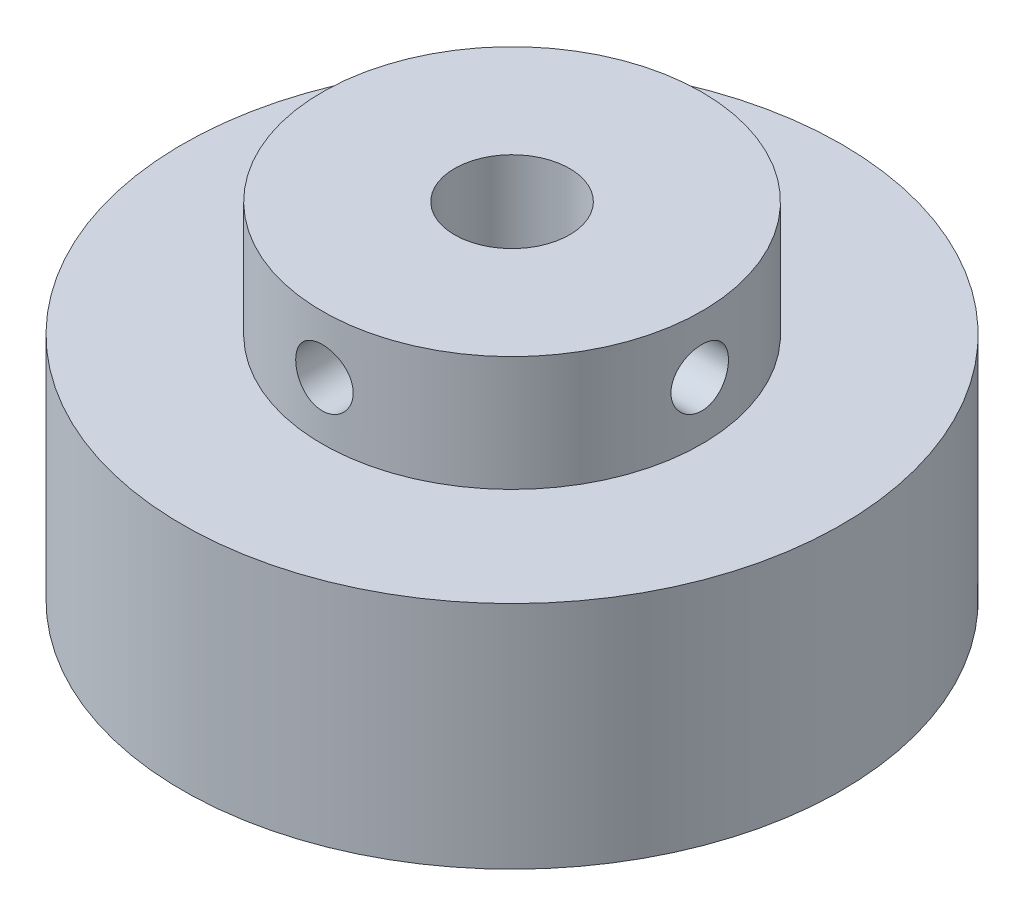
SolidWorks part; units mm, degrees
material "AISI 1020"
ref_plane "Alzado" through (0, 0, 0) normal (0, 0, 1) x (1, 0, 0)
ref_plane "Planta" through (0, 0, 0) normal (0, 1, 0) x (1, 0, 0)
ref_plane "Vista lateral" through (0, 0, 0) normal (1, 0, 0) x (0, 0, -1)
sketch "Croquis1" plane through (0, 0, 0) normal (0, 0, 1) x (1, 0, 0)
  line L0 (0, 0) -> (0, 49.1188) construction
  line L1 (-4, 0) -> (-4, 30)
  line L2 (-4, 30) -> (-16.5, 30)
  line L3 (-16.5, 30) -> (-16.5, 20)
  line L4 (-16.5, 20) -> (-28.65, 20)
  line L5 (-28.65, 20) -> (-28.65, 0)
  line L6 (-28.65, 0) -> (-4, 0)
  line L7 (0, 0) -> (29.4511, 0) construction
  dimension "D1" = 4
  dimension "D2" = 16.5
  dimension "D3" = 28.65
  dimension "D4" = 20
  dimension "D5" = 10
revolve "Revolución1" add sketch "Croquis1" angle 360 about L0
sketch "Croquis2" plane through (0, 0, 0) normal (0, -1, 0) x (-1, 0, 0)
  line L0 (0, 0) -> (0, -28.65) construction
  line L1 (0, 0) -> (-2.9947, -28.4931) construction
  line L2 (0, 0) -> (-5.9567, -28.0239) construction
  line L3 (0, 0) -> (-8.8533, -27.2478) construction
  line L4 (0, 0) -> (-11.653, -26.1731) construction
  line L5 (0, 0) -> (-14.325, -24.8116) construction
  line L6 (0, 0) -> (-16.84, -23.1783) construction
  line L7 (0, 0) -> (-19.1706, -21.2911) construction
  line L8 (0, 0) -> (-21.2911, -19.1706) construction
  line L9 (0, 0) -> (-23.1783, -16.84) construction
  line L10 (0, 0) -> (-24.8116, -14.325) construction
  line L11 (0, 0) -> (-26.1731, -11.653) construction
  line L12 (0, 0) -> (-27.2478, -8.8533) construction
  line L13 (0, 0) -> (-28.0239, -5.9567) construction
  line L14 (0, 0) -> (-28.4931, -2.9947) construction
  line L15 (0, 0) -> (-28.65, 0) construction
  line L16 (0, 0) -> (-28.4931, 2.9947) construction
  line L17 (0, 0) -> (-28.0239, 5.9567) construction
  line L18 (0, 0) -> (-27.2478, 8.8533) construction
  line L19 (0, 0) -> (-26.1731, 11.653) construction
  line L20 (0, 0) -> (-24.8116, 14.325) construction
  line L21 (0, 0) -> (-23.1783, 16.84) construction
  line L22 (0, 0) -> (-21.2911, 19.1706) construction
  line L23 (0, 0) -> (-19.1706, 21.2911) construction
  line L24 (0, 0) -> (-16.84, 23.1783) construction
  line L25 (0, 0) -> (-14.325, 24.8116) construction
  line L26 (0, 0) -> (-11.653, 26.1731) construction
  line L27 (0, 0) -> (-8.8533, 27.2478) construction
  line L28 (0, 0) -> (-5.9567, 28.0239) construction
  line L29 (0, 0) -> (-2.9947, 28.4931) construction
  line L30 (0, 0) -> (0, 28.65) construction
  line L31 (0, 0) -> (2.9947, 28.4931) construction
  line L32 (0, 0) -> (5.9567, 28.0239) construction
  line L33 (0, 0) -> (8.8533, 27.2478) construction
  line L34 (0, 0) -> (11.653, 26.1731) construction
  line L35 (0, 0) -> (14.325, 24.8116) construction
  line L36 (0, 0) -> (16.84, 23.1783) construction
  line L37 (0, 0) -> (19.1706, 21.2911) construction
  line L38 (0, 0) -> (21.2911, 19.1706) construction
  line L39 (0, 0) -> (23.1783, 16.84) construction
  line L40 (0, 0) -> (24.8116, 14.325) construction
  line L41 (0, 0) -> (26.1731, 11.653) construction
  line L42 (0, 0) -> (27.2478, 8.8533) construction
  line L43 (0, 0) -> (28.0239, 5.9567) construction
  line L44 (0, 0) -> (28.4931, 2.9947) construction
  line L45 (0, 0) -> (28.65, 0) construction
  line L46 (0, 0) -> (28.4931, -2.9947) construction
  line L47 (0, 0) -> (28.0239, -5.9567) construction
  line L48 (0, 0) -> (27.2478, -8.8533) construction
  line L49 (0, 0) -> (26.1731, -11.653) construction
  line L50 (0, 0) -> (24.8116, -14.325) construction
  line L51 (0, 0) -> (23.1783, -16.84) construction
  line L52 (0, 0) -> (21.2911, -19.1706) construction
  line L53 (0, 0) -> (19.1706, -21.2911) construction
  line L54 (0, 0) -> (16.84, -23.1783) construction
  line L55 (0, 0) -> (14.325, -24.8116) construction
  line L56 (0, 0) -> (11.653, -26.1731) construction
  line L57 (0, 0) -> (8.8533, -27.2478) construction
  line L58 (0, 0) -> (5.9567, -28.0239) construction
  line L59 (0, 0) -> (2.9947, -28.4931) construction
  line L60 (-2.9947, -28.4931) -> (-4.4757, -28.2585) construction
  line L61 (-4.4757, -28.2585) -> (-4.6343, -29.2598) construction
  line L62 (-3.7352, -28.3758) -> (-3.82, -28.911) construction
  line L63 (-4.4757, -28.2585) -> (-4.3108, -27.217) construction
  line L64 (-2.9947, -28.4931) -> (-3.1525, -29.994) construction
  circle A0 centre (0, 0) radius 28.65 construction
  arc A1 (-3.7352, -28.3758) -> (-2.2461, -28.5323) centre (-2.9947, -28.4931) ccw
  arc A2 (-3.7352, -28.3758) -> (-4.3584, -27.518) centre (-4.4757, -28.2585) ccw
  arc A3 (-2.2461, -28.5323) -> (-1.4581, -27.8228) centre (-1.4974, -28.5715) cw
  arc A4 (-5.2162, -28.1412) -> (-4.3584, -27.518) centre (-4.4757, -28.2585) cw
  arc A5 (-6.6808, -27.8299) -> (-5.2162, -28.1412) centre (-5.9567, -28.0239) ccw
  arc A6 (-6.6808, -27.8299) -> (-7.211, -26.9117) centre (-7.405, -27.6358) ccw
  arc A7 (-8.1292, -27.4418) -> (-7.211, -26.9117) centre (-7.405, -27.6358) cw
  arc A8 (-9.5533, -26.9791) -> (-8.1292, -27.4418) centre (-8.8533, -27.2478) ccw
  arc A9 (-9.5533, -26.9791) -> (-9.9845, -26.0105) centre (-10.2532, -26.7104) ccw
  arc A10 (-10.9531, -26.4418) -> (-9.9845, -26.0105) centre (-10.2532, -26.7104) cw
  arc A11 (-12.321, -25.8327) -> (-10.9531, -26.4418) centre (-11.653, -26.1731) ccw
  arc A12 (-12.321, -25.8327) -> (-12.6486, -24.8244) centre (-12.989, -25.4924) ccw
  arc A13 (-13.657, -25.152) -> (-12.6486, -24.8244) centre (-12.989, -25.4924) cw
  arc A14 (-14.9538, -24.4033) -> (-13.657, -25.152) centre (-14.325, -24.8116) ccw
  arc A15 (-14.9538, -24.4033) -> (-15.1742, -23.3662) centre (-15.5825, -23.995) ccw
  arc A16 (-16.2113, -23.5867) -> (-15.1742, -23.3662) centre (-15.5825, -23.995) cw
  arc A17 (-17.4227, -22.7065) -> (-16.2113, -23.5867) centre (-16.84, -23.1783) ccw
  arc A18 (-17.4227, -22.7065) -> (-17.5335, -21.6521) centre (-18.0053, -22.2347) ccw
  arc A19 (-18.588, -21.7629) -> (-17.5335, -21.6521) centre (-18.0053, -22.2347) cw
  arc A20 (-19.7007, -20.761) -> (-18.588, -21.7629) centre (-19.1706, -21.2911) ccw
  arc A21 (-19.7007, -20.761) -> (-19.7007, -19.7007) centre (-20.2308, -20.2308) ccw
  arc A22 (-20.761, -19.7007) -> (-19.7007, -19.7007) centre (-20.2308, -20.2308) cw
  arc A23 (-21.7629, -18.588) -> (-20.761, -19.7007) centre (-21.2911, -19.1706) ccw
  arc A24 (-21.7629, -18.588) -> (-21.6521, -17.5335) centre (-22.2347, -18.0053) ccw
  arc A25 (-22.7065, -17.4227) -> (-21.6521, -17.5335) centre (-22.2347, -18.0053) cw
  arc A26 (-23.5867, -16.2113) -> (-22.7065, -17.4227) centre (-23.1783, -16.84) ccw
  arc A27 (-23.5867, -16.2113) -> (-23.3662, -15.1742) centre (-23.995, -15.5825) ccw
  arc A28 (-24.4033, -14.9538) -> (-23.3662, -15.1742) centre (-23.995, -15.5825) cw
  arc A29 (-25.152, -13.657) -> (-24.4033, -14.9538) centre (-24.8116, -14.325) ccw
  arc A30 (-25.152, -13.657) -> (-24.8244, -12.6486) centre (-25.4924, -12.989) ccw
  arc A31 (-25.8327, -12.321) -> (-24.8244, -12.6486) centre (-25.4924, -12.989) cw
  arc A32 (-26.4418, -10.9531) -> (-25.8327, -12.321) centre (-26.1731, -11.653) ccw
  arc A33 (-26.4418, -10.9531) -> (-26.0105, -9.9845) centre (-26.7104, -10.2532) ccw
  arc A34 (-26.9791, -9.5533) -> (-26.0105, -9.9845) centre (-26.7104, -10.2532) cw
  arc A35 (-27.4418, -8.1292) -> (-26.9791, -9.5533) centre (-27.2478, -8.8533) ccw
  arc A36 (-27.4418, -8.1292) -> (-26.9117, -7.211) centre (-27.6358, -7.405) ccw
  arc A37 (-27.8299, -6.6808) -> (-26.9117, -7.211) centre (-27.6358, -7.405) cw
  arc A38 (-28.1412, -5.2162) -> (-27.8299, -6.6808) centre (-28.0239, -5.9567) ccw
  arc A39 (-28.1412, -5.2162) -> (-27.518, -4.3584) centre (-28.2585, -4.4757) ccw
  arc A40 (-28.3758, -3.7352) -> (-27.518, -4.3584) centre (-28.2585, -4.4757) cw
  arc A41 (-28.5323, -2.2461) -> (-28.3758, -3.7352) centre (-28.4931, -2.9947) ccw
  arc A42 (-28.5323, -2.2461) -> (-27.8228, -1.4581) centre (-28.5715, -1.4974) ccw
  arc A43 (-28.6108, -0.7487) -> (-27.8228, -1.4581) centre (-28.5715, -1.4974) cw
  arc A44 (-28.6108, 0.7487) -> (-28.6108, -0.7487) centre (-28.65, 0) ccw
  arc A45 (-28.6108, 0.7487) -> (-27.8228, 1.4581) centre (-28.5715, 1.4974) ccw
  arc A46 (-28.5323, 2.2461) -> (-27.8228, 1.4581) centre (-28.5715, 1.4974) cw
  arc A47 (-28.3758, 3.7352) -> (-28.5323, 2.2461) centre (-28.4931, 2.9947) ccw
  arc A48 (-28.3758, 3.7352) -> (-27.518, 4.3584) centre (-28.2585, 4.4757) ccw
  arc A49 (-28.1412, 5.2162) -> (-27.518, 4.3584) centre (-28.2585, 4.4757) cw
  arc A50 (-27.8299, 6.6808) -> (-28.1412, 5.2162) centre (-28.0239, 5.9567) ccw
  arc A51 (-27.8299, 6.6808) -> (-26.9117, 7.211) centre (-27.6358, 7.405) ccw
  arc A52 (-27.4418, 8.1292) -> (-26.9117, 7.211) centre (-27.6358, 7.405) cw
  arc A53 (-26.9791, 9.5533) -> (-27.4418, 8.1292) centre (-27.2478, 8.8533) ccw
  arc A54 (-26.9791, 9.5533) -> (-26.0105, 9.9845) centre (-26.7104, 10.2532) ccw
  arc A55 (-26.4418, 10.9531) -> (-26.0105, 9.9845) centre (-26.7104, 10.2532) cw
  arc A56 (-25.8327, 12.321) -> (-26.4418, 10.9531) centre (-26.1731, 11.653) ccw
  arc A57 (-25.8327, 12.321) -> (-24.8244, 12.6486) centre (-25.4924, 12.989) ccw
  arc A58 (-25.152, 13.657) -> (-24.8244, 12.6486) centre (-25.4924, 12.989) cw
  arc A59 (-24.4033, 14.9538) -> (-25.152, 13.657) centre (-24.8116, 14.325) ccw
  arc A60 (-24.4033, 14.9538) -> (-23.3662, 15.1742) centre (-23.995, 15.5825) ccw
  arc A61 (-23.5867, 16.2113) -> (-23.3662, 15.1742) centre (-23.995, 15.5825) cw
  arc A62 (-22.7065, 17.4227) -> (-23.5867, 16.2113) centre (-23.1783, 16.84) ccw
  arc A63 (-22.7065, 17.4227) -> (-21.6521, 17.5335) centre (-22.2347, 18.0053) ccw
  arc A64 (-21.7629, 18.588) -> (-21.6521, 17.5335) centre (-22.2347, 18.0053) cw
  arc A65 (-20.761, 19.7007) -> (-21.7629, 18.588) centre (-21.2911, 19.1706) ccw
  arc A66 (-20.761, 19.7007) -> (-19.7007, 19.7007) centre (-20.2308, 20.2308) ccw
  arc A67 (-19.7007, 20.761) -> (-19.7007, 19.7007) centre (-20.2308, 20.2308) cw
  arc A68 (-18.588, 21.7629) -> (-19.7007, 20.761) centre (-19.1706, 21.2911) ccw
  arc A69 (-18.588, 21.7629) -> (-17.5335, 21.6521) centre (-18.0053, 22.2347) ccw
  arc A70 (-17.4227, 22.7065) -> (-17.5335, 21.6521) centre (-18.0053, 22.2347) cw
  arc A71 (-16.2113, 23.5867) -> (-17.4227, 22.7065) centre (-16.84, 23.1783) ccw
  arc A72 (-16.2113, 23.5867) -> (-15.1742, 23.3662) centre (-15.5825, 23.995) ccw
  arc A73 (-14.9538, 24.4033) -> (-15.1742, 23.3662) centre (-15.5825, 23.995) cw
  arc A74 (-13.657, 25.152) -> (-14.9538, 24.4033) centre (-14.325, 24.8116) ccw
  arc A75 (-13.657, 25.152) -> (-12.6486, 24.8244) centre (-12.989, 25.4924) ccw
  arc A76 (-12.321, 25.8327) -> (-12.6486, 24.8244) centre (-12.989, 25.4924) cw
  arc A77 (-10.9531, 26.4418) -> (-12.321, 25.8327) centre (-11.653, 26.1731) ccw
  arc A78 (-10.9531, 26.4418) -> (-9.9845, 26.0105) centre (-10.2532, 26.7104) ccw
  arc A79 (-9.5533, 26.9791) -> (-9.9845, 26.0105) centre (-10.2532, 26.7104) cw
  arc A80 (-8.1292, 27.4418) -> (-9.5533, 26.9791) centre (-8.8533, 27.2478) ccw
  arc A81 (-8.1292, 27.4418) -> (-7.211, 26.9117) centre (-7.405, 27.6358) ccw
  arc A82 (-6.6808, 27.8299) -> (-7.211, 26.9117) centre (-7.405, 27.6358) cw
  arc A83 (-5.2162, 28.1412) -> (-6.6808, 27.8299) centre (-5.9567, 28.0239) ccw
  arc A84 (-5.2162, 28.1412) -> (-4.3584, 27.518) centre (-4.4757, 28.2585) ccw
  arc A85 (-3.7352, 28.3758) -> (-4.3584, 27.518) centre (-4.4757, 28.2585) cw
  arc A86 (-2.2461, 28.5323) -> (-3.7352, 28.3758) centre (-2.9947, 28.4931) ccw
  arc A87 (-2.2461, 28.5323) -> (-1.4581, 27.8228) centre (-1.4974, 28.5715) ccw
  arc A88 (-0.7487, 28.6108) -> (-1.4581, 27.8228) centre (-1.4974, 28.5715) cw
  arc A89 (0.7487, 28.6108) -> (-0.7487, 28.6108) centre (0, 28.65) ccw
  arc A90 (0.7487, 28.6108) -> (1.4581, 27.8228) centre (1.4974, 28.5715) ccw
  arc A91 (2.2461, 28.5323) -> (1.4581, 27.8228) centre (1.4974, 28.5715) cw
  arc A92 (3.7352, 28.3758) -> (2.2461, 28.5323) centre (2.9947, 28.4931) ccw
  arc A93 (3.7352, 28.3758) -> (4.3584, 27.518) centre (4.4757, 28.2585) ccw
  arc A94 (5.2162, 28.1412) -> (4.3584, 27.518) centre (4.4757, 28.2585) cw
  arc A95 (6.6808, 27.8299) -> (5.2162, 28.1412) centre (5.9567, 28.0239) ccw
  arc A96 (6.6808, 27.8299) -> (7.211, 26.9117) centre (7.405, 27.6358) ccw
  arc A97 (8.1292, 27.4418) -> (7.211, 26.9117) centre (7.405, 27.6358) cw
  arc A98 (9.5533, 26.9791) -> (8.1292, 27.4418) centre (8.8533, 27.2478) ccw
  arc A99 (9.5533, 26.9791) -> (9.9845, 26.0105) centre (10.2532, 26.7104) ccw
  arc A100 (10.9531, 26.4418) -> (9.9845, 26.0105) centre (10.2532, 26.7104) cw
  arc A101 (12.321, 25.8327) -> (10.9531, 26.4418) centre (11.653, 26.1731) ccw
  arc A102 (12.321, 25.8327) -> (12.6486, 24.8244) centre (12.989, 25.4924) ccw
  arc A103 (13.657, 25.152) -> (12.6486, 24.8244) centre (12.989, 25.4924) cw
  arc A104 (14.9538, 24.4033) -> (13.657, 25.152) centre (14.325, 24.8116) ccw
  arc A105 (14.9538, 24.4033) -> (15.1742, 23.3662) centre (15.5825, 23.995) ccw
  arc A106 (16.2113, 23.5867) -> (15.1742, 23.3662) centre (15.5825, 23.995) cw
  arc A107 (17.4227, 22.7065) -> (16.2113, 23.5867) centre (16.84, 23.1783) ccw
  arc A108 (17.4227, 22.7065) -> (17.5335, 21.6521) centre (18.0053, 22.2347) ccw
  arc A109 (18.588, 21.7629) -> (17.5335, 21.6521) centre (18.0053, 22.2347) cw
  arc A110 (19.7007, 20.761) -> (18.588, 21.7629) centre (19.1706, 21.2911) ccw
  arc A111 (19.7007, 20.761) -> (19.7007, 19.7007) centre (20.2308, 20.2308) ccw
  arc A112 (20.761, 19.7007) -> (19.7007, 19.7007) centre (20.2308, 20.2308) cw
  arc A113 (21.7629, 18.588) -> (20.761, 19.7007) centre (21.2911, 19.1706) ccw
  arc A114 (21.7629, 18.588) -> (21.6521, 17.5335) centre (22.2347, 18.0053) ccw
  arc A115 (22.7065, 17.4227) -> (21.6521, 17.5335) centre (22.2347, 18.0053) cw
  arc A116 (23.5867, 16.2113) -> (22.7065, 17.4227) centre (23.1783, 16.84) ccw
  arc A117 (23.5867, 16.2113) -> (23.3662, 15.1742) centre (23.995, 15.5825) ccw
  arc A118 (24.4033, 14.9538) -> (23.3662, 15.1742) centre (23.995, 15.5825) cw
  arc A119 (25.152, 13.657) -> (24.4033, 14.9538) centre (24.8116, 14.325) ccw
  arc A120 (25.152, 13.657) -> (24.8244, 12.6486) centre (25.4924, 12.989) ccw
  arc A121 (25.8327, 12.321) -> (24.8244, 12.6486) centre (25.4924, 12.989) cw
  arc A122 (26.4418, 10.9531) -> (25.8327, 12.321) centre (26.1731, 11.653) ccw
  arc A123 (26.4418, 10.9531) -> (26.0105, 9.9845) centre (26.7104, 10.2532) ccw
  arc A124 (26.9791, 9.5533) -> (26.0105, 9.9845) centre (26.7104, 10.2532) cw
  arc A125 (27.4418, 8.1292) -> (26.9791, 9.5533) centre (27.2478, 8.8533) ccw
  arc A126 (27.4418, 8.1292) -> (26.9117, 7.211) centre (27.6358, 7.405) ccw
  arc A127 (27.8299, 6.6808) -> (26.9117, 7.211) centre (27.6358, 7.405) cw
  arc A128 (28.1412, 5.2162) -> (27.8299, 6.6808) centre (28.0239, 5.9567) ccw
  arc A129 (28.1412, 5.2162) -> (27.518, 4.3584) centre (28.2585, 4.4757) ccw
  arc A130 (28.3758, 3.7352) -> (27.518, 4.3584) centre (28.2585, 4.4757) cw
  arc A131 (28.5323, 2.2461) -> (28.3758, 3.7352) centre (28.4931, 2.9947) ccw
  arc A132 (28.5323, 2.2461) -> (27.8228, 1.4581) centre (28.5715, 1.4974) ccw
  arc A133 (28.6108, 0.7487) -> (27.8228, 1.4581) centre (28.5715, 1.4974) cw
  arc A134 (28.6108, -0.7487) -> (28.6108, 0.7487) centre (28.65, 0) ccw
  arc A135 (28.6108, -0.7487) -> (27.8228, -1.4581) centre (28.5715, -1.4974) ccw
  arc A136 (28.5323, -2.2461) -> (27.8228, -1.4581) centre (28.5715, -1.4974) cw
  arc A137 (28.3758, -3.7352) -> (28.5323, -2.2461) centre (28.4931, -2.9947) ccw
  arc A138 (28.3758, -3.7352) -> (27.518, -4.3584) centre (28.2585, -4.4757) ccw
  arc A139 (28.1412, -5.2162) -> (27.518, -4.3584) centre (28.2585, -4.4757) cw
  arc A140 (27.8299, -6.6808) -> (28.1412, -5.2162) centre (28.0239, -5.9567) ccw
  arc A141 (27.8299, -6.6808) -> (26.9117, -7.211) centre (27.6358, -7.405) ccw
  arc A142 (27.4418, -8.1292) -> (26.9117, -7.211) centre (27.6358, -7.405) cw
  arc A143 (26.9791, -9.5533) -> (27.4418, -8.1292) centre (27.2478, -8.8533) ccw
  arc A144 (26.9791, -9.5533) -> (26.0105, -9.9845) centre (26.7104, -10.2532) ccw
  arc A145 (26.4418, -10.9531) -> (26.0105, -9.9845) centre (26.7104, -10.2532) cw
  arc A146 (25.8327, -12.321) -> (26.4418, -10.9531) centre (26.1731, -11.653) ccw
  arc A147 (25.8327, -12.321) -> (24.8244, -12.6486) centre (25.4924, -12.989) ccw
  arc A148 (25.152, -13.657) -> (24.8244, -12.6486) centre (25.4924, -12.989) cw
  arc A149 (24.4033, -14.9538) -> (25.152, -13.657) centre (24.8116, -14.325) ccw
  arc A150 (24.4033, -14.9538) -> (23.3662, -15.1742) centre (23.995, -15.5825) ccw
  arc A151 (23.5867, -16.2113) -> (23.3662, -15.1742) centre (23.995, -15.5825) cw
  arc A152 (22.7065, -17.4227) -> (23.5867, -16.2113) centre (23.1783, -16.84) ccw
  arc A153 (22.7065, -17.4227) -> (21.6521, -17.5335) centre (22.2347, -18.0053) ccw
  arc A154 (21.7629, -18.588) -> (21.6521, -17.5335) centre (22.2347, -18.0053) cw
  arc A155 (20.761, -19.7007) -> (21.7629, -18.588) centre (21.2911, -19.1706) ccw
  arc A156 (20.761, -19.7007) -> (19.7007, -19.7007) centre (20.2308, -20.2308) ccw
  arc A157 (19.7007, -20.761) -> (19.7007, -19.7007) centre (20.2308, -20.2308) cw
  arc A158 (18.588, -21.7629) -> (19.7007, -20.761) centre (19.1706, -21.2911) ccw
  arc A159 (18.588, -21.7629) -> (17.5335, -21.6521) centre (18.0053, -22.2347) ccw
  arc A160 (17.4227, -22.7065) -> (17.5335, -21.6521) centre (18.0053, -22.2347) cw
  arc A161 (16.2113, -23.5867) -> (17.4227, -22.7065) centre (16.84, -23.1783) ccw
  arc A162 (16.2113, -23.5867) -> (15.1742, -23.3662) centre (15.5825, -23.995) ccw
  arc A163 (14.9538, -24.4033) -> (15.1742, -23.3662) centre (15.5825, -23.995) cw
  arc A164 (13.657, -25.152) -> (14.9538, -24.4033) centre (14.325, -24.8116) ccw
  arc A165 (13.657, -25.152) -> (12.6486, -24.8244) centre (12.989, -25.4924) ccw
  arc A166 (12.321, -25.8327) -> (12.6486, -24.8244) centre (12.989, -25.4924) cw
  arc A167 (10.9531, -26.4418) -> (12.321, -25.8327) centre (11.653, -26.1731) ccw
  arc A168 (10.9531, -26.4418) -> (9.9845, -26.0105) centre (10.2532, -26.7104) ccw
  arc A169 (9.5533, -26.9791) -> (9.9845, -26.0105) centre (10.2532, -26.7104) cw
  arc A170 (8.1292, -27.4418) -> (9.5533, -26.9791) centre (8.8533, -27.2478) ccw
  arc A171 (8.1292, -27.4418) -> (7.211, -26.9117) centre (7.405, -27.6358) ccw
  arc A172 (6.6808, -27.8299) -> (7.211, -26.9117) centre (7.405, -27.6358) cw
  arc A173 (5.2162, -28.1412) -> (6.6808, -27.8299) centre (5.9567, -28.0239) ccw
  arc A174 (5.2162, -28.1412) -> (4.3584, -27.518) centre (4.4757, -28.2585) ccw
  arc A175 (3.7352, -28.3758) -> (4.3584, -27.518) centre (4.4757, -28.2585) cw
  arc A176 (2.2461, -28.5323) -> (3.7352, -28.3758) centre (2.9947, -28.4931) ccw
  arc A177 (2.2461, -28.5323) -> (1.4581, -27.8228) centre (1.4974, -28.5715) ccw
  arc A178 (0.7487, -28.6108) -> (1.4581, -27.8228) centre (1.4974, -28.5715) cw
  arc A179 (-0.7487, -28.6108) -> (0.7487, -28.6108) centre (0, -28.65) ccw
  arc A180 (-0.7487, -28.6108) -> (-1.4581, -27.8228) centre (-1.4974, -28.5715) ccw
  point P67 (0, 0)
  point P491 (0, 0)
  dimension "D2" = 1.4994
  dimension "D3" = 0.7497
  dimension "D1" = 60
  dimension "D4" = 60
sketch "Croquis3" plane through (0, 30, 0) normal (0, 1, 0) x (1, 0, 0)
  circle A0 centre (0, 0) radius 5
  dimension "D1" = 10
extrude "Cortar-Extruir1" cut sketch "Croquis3" against normal through all
ref_plane "Plano1" through (16.5, 0, 0) normal (1, 0, 0) x (0, 0, -1)
sketch "Croquis4" plane through (16.5, 0, 0) normal (1, 0, 0) x (0, 0, -1)
  line L0 (0, 30) -> (0, 20) construction
  line L1 (16.5, 30) -> (-16.5, 30) construction
  line L2 (28.65, 20) -> (-28.65, 20) construction
  point P0 (0, 25)
  point P7 (0, 25)
hole_wizard "Taladro roscado M6x1.01" positions "Croquis5" profile "Croquis6" tap size "M6x1.0" standard "Ansi Metric"
sketch "Croquis5" plane through (16.5, 0, 0) normal (1, 0, 0) x (0, 0, -1)
  point P0 (0, 25)
sketch "Croquis6" plane through (16.5, 25, 0) normal (0, 1, 0) x (0, 0, -1)
  line L0 (0, 0) -> (0, 18.5022)
  line L1 (0, 18.5022) -> (2.5, 17)
  line L2 (2.5, 17) -> (2.5, 0)
  line L5 (2.5, 0) -> (0, 0)
  line L10 (0, 18.5022) -> (-2.5, 17) construction
  line L11 (0, -6.35) -> (0, 107.95) construction
  dimension "Diámetro de perforador para roscar" = 5
  dimension "Profundidad de perforador para roscar" = 17
  dimension "Ángulo de perforador" = 118
cosmetic thread "Rosca de taladro1" parameters "D1"=12, "D2"=6
pattern_circular "MatrizC1" count 2 over 90 about axis through (0, 30, 0) along (0, -1, 0) of "Taladro roscado M6x1.01"
